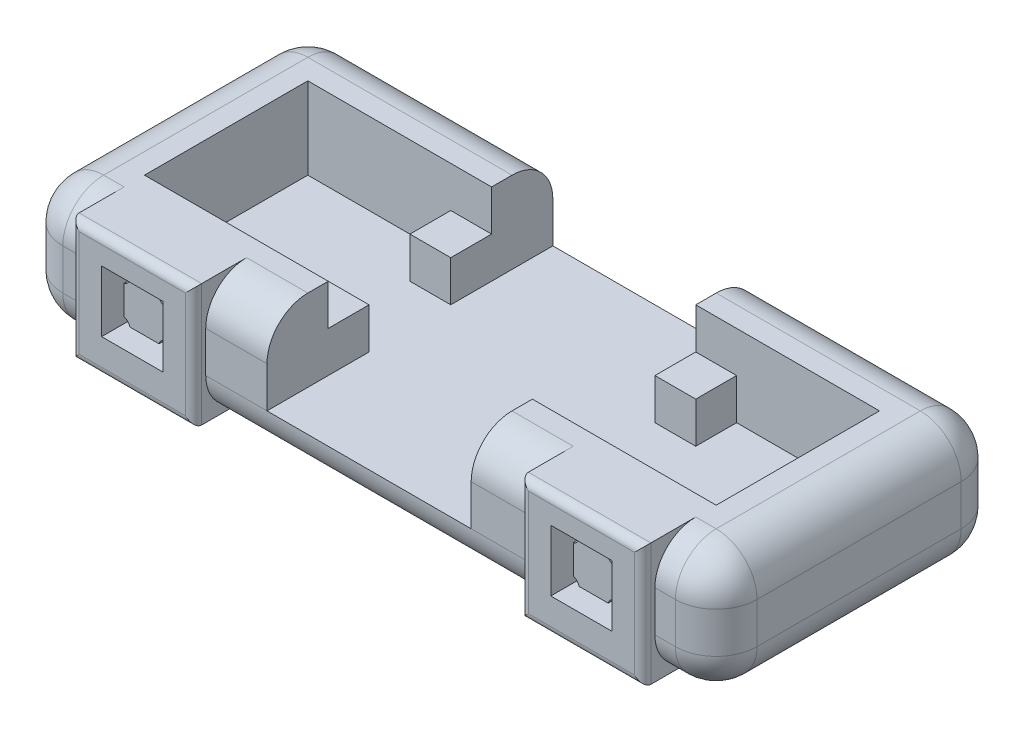
SolidWorks part; units mm, degrees
ref_plane "Front Plane" through (0, 0, 0) normal (0, 0, 1) x (1, 0, 0)
ref_plane "Top Plane" through (0, 0, 0) normal (0, 1, 0) x (1, 0, 0)
ref_plane "Right Plane" through (0, 0, 0) normal (1, 0, 0) x (0, 0, -1)
sketch "Sketch1" plane through (0, 0, 0) normal (0, 1, 0) x (1, 0, 0)
  line L1 (-85, -35) -> (85, -35)
  line L2 (-85, -35) -> (-85, 35)
  line L3 (-85, 35) -> (85, 35)
  line L4 (85, -35) -> (85, 35)
  line L5 (-85, -35) -> (85, 35) construction
  line L6 (-85, 35) -> (85, -35) construction
  point P0 (0, 0)
  dimension "D1" = 170
  dimension "D2" = 70
extrude "Boss-Extrude1" add sketch "Sketch1" along normal blind 30
fillet "Fillet1" radius 10 12 edges at (-85, 30, 0) (0, 30, 35) (-85, 15, 35) (85, 0, 0) (0, 0, -35) (-85, 0, 0) (0, 0, 35) (85, 30, 0) (0, 30, -35) (85, 15, 35) (-85, 15, -35) (85, 15, -35)
sketch "Sketch2" plane through (0, 30, 0) normal (0, 1, 0) x (1, 0, 0)
  line L0 (-75, 35) -> (75, 35) construction
  line L1 (25, -35) -> (-25, -35)
  line L2 (25, -35) -> (25, 35)
  line L3 (25, 35) -> (-25, 35)
  line L4 (-25, -35) -> (-25, 35)
  line L5 (25, -35) -> (-25, 35) construction
  line L6 (25, 35) -> (-25, -35) construction
  line L8 (70, -20) -> (-70, -20)
  line L9 (70, -20) -> (70, 20)
  line L10 (70, 20) -> (-70, 20)
  line L11 (-70, -20) -> (-70, 20)
  line L12 (70, -20) -> (-70, 20) construction
  line L13 (70, 20) -> (-70, -20) construction
  point P0 (0, 0)
  point P8 (0, 0)
  line M9 (75, 25) -> (-75, 25)
  line M11 (-75, -25) -> (75, -25)
  dimension "D1" = 50
  dimension "D2" = 140
  dimension "D3" = 40
extrude "Cut-Extrude1" cut sketch "Sketch2" against normal blind 20 contours L11 L8 L4 L10 | L2 L10 L4 L8 | L9 L10 L2 L8 | L4 L2 L3 M9 | L10 L2 L4 M9 | L4 L1 L2 M11 | L2 L8 L4 M11
sketch "Sketch3" plane through (0, 10, 0) normal (0, 1, 0) x (1, 0, 0)
  line L1 (-25, 20) -> (-35, 20)
  line L2 (-25, 20) -> (-25, 10)
  line L3 (-25, 10) -> (-35, 10)
  line L4 (-35, 20) -> (-35, 10)
  line L5 (25, 20) -> (35, 20)
  line L6 (25, 20) -> (25, 10)
  line L7 (25, 10) -> (35, 10)
  line L8 (35, 20) -> (35, 10)
  line L9 (25, -20) -> (35, -20)
  line L10 (25, -20) -> (25, -10)
  line L11 (25, -10) -> (35, -10)
  line L12 (35, -20) -> (35, -10)
  line L13 (-25, -20) -> (-35, -20)
  line L14 (-25, -20) -> (-25, -10)
  line L15 (-25, -10) -> (-35, -10)
  line L16 (-35, -20) -> (-35, -10)
  dimension "D1" = 10
  dimension "D2" = 10
  dimension "D3" = 10
  dimension "D4" = 10
  dimension "D5" = 10
  dimension "D6" = 10
  dimension "D7" = 10
  dimension "D8" = 10
extrude "Boss-Extrude2" add sketch "Sketch3" along normal blind 10
sketch "Sketch4" plane through (0, 0, 35) normal (0, 0, 1) x (1, 0, 0)
  line L0 (-25, 10) -> (-25, 20) construction
  line L2 (0, 0) -> (0, 30) construction
  line L3 (40, 30) -> (70, 30)
  line L4 (70, 0) -> (70, 30)
  line L5 (40, 0) -> (70, 0)
  line L6 (40, 0) -> (40, 30)
  line L8 (-68.0808, 30) -> (-70, 30)
  line L9 (-75, 30) -> (-25, 30) construction
  line L14 (-40, 0) -> (-70, 0)
  line L15 (-40, 0) -> (-40, 30)
  line L16 (-40, 30) -> (-70, 30)
  line L17 (-70, 0) -> (-70, 30)
  point P10 (-55, 15)
  line M6 (75, 20) -> (25, 20)
  line M8 (25, 10) -> (75, 10)
  dimension "D1" = 30
  dimension "D2" = 30
  dimension "D3" = 15
extrude "Boss-Extrude3" add sketch "Sketch4" along normal blind 3 contours L17 L14 L15 L16 L8 | L6 L4 M8 M6 | L6 L4 L3 M6 | L6 L5 L4 M8
sketch "Sketch5" plane through (0, 0, 35) normal (0, 0, -1) x (-1, 0, 0)
  line L1 (-70, 30) -> (-40, 30)
  line L2 (-70, 30) -> (-70, 0)
  line L3 (-70, 0) -> (-40, 0)
  line L4 (-40, 30) -> (-40, 0)
  line L5 (40, 0) -> (70, 0)
  line L6 (40, 0) -> (40, 30)
  line L7 (40, 30) -> (70, 30)
  line L8 (70, 0) -> (70, 30)
extrude "Boss-Extrude4" add sketch "Sketch5" along normal blind 10
fillet "Fillet2" radius 2 8 edges at (-55, 30, 38) (-40, 15, 38) (-55, 0, 38) (-70, 15, 38) (55, 30, 38) (70, 15, 38) (55, 0, 38) (40, 15, 38)
sketch "Sketch6" plane through (0, 0, 38) normal (0, 0, 1) x (1, 0, 0)
  line L0 (-70, 30) -> (-40, 30) construction
  line L1 (-47.5, 8.5) -> (-62.5, 8.5)
  line L2 (-47.5, 8.5) -> (-47.5, 23.5)
  line L7 (-47.5, 23.5) -> (-62.5, 23.5)
  line L8 (-62.5, 8.5) -> (-62.5, 23.5)
  line L13 (-47.5, 8.5) -> (-62.5, 23.5) construction
  line L14 (-47.5, 23.5) -> (-62.5, 8.5) construction
  line L16 (0, 0) -> (0, 27.2097) construction
  line L17 (47.5, 23.5) -> (62.5, 23.5)
  line L18 (62.5, 8.5) -> (62.5, 23.5)
  line L19 (47.5, 8.5) -> (62.5, 8.5)
  line L20 (47.5, 8.5) -> (47.5, 23.5)
  line L21 (-70, 10) -> (-70, 20) construction
  point P0 (-55, 16)
  point P8 (-55, 16)
  dimension "D1" = 15
  dimension "D2" = 15
  dimension "D3" = 6.5
  dimension "D4" = 7.5
extrude "Cut-Extrude2" cut sketch "Sketch6" against normal blind 10
sketch "Sketch7" plane through (0, 0, 28) normal (0, 0, 1) x (1, 0, 0)
  line L0 (-62.5, 8.5) -> (-47.5, 23.5) construction
  line L1 (-62.5, 23.5) -> (-47.5, 8.5) construction
  line L2 (0, 0) -> (0, 29.8269) construction
  line L3 (-50, 11) -> (-60, 11)
  line L4 (-50, 11) -> (-50, 21)
  line L5 (-50, 21) -> (-60, 21)
  line L6 (-60, 11) -> (-60, 21)
  line L7 (-50, 11) -> (-60, 21) construction
  line L8 (-50, 21) -> (-60, 11) construction
  line L9 (40, 0) -> (-40, 0) construction
  line L10 (50, 21) -> (60, 21)
  line L11 (60, 11) -> (60, 21)
  line L12 (50, 11) -> (60, 11)
  line L13 (50, 11) -> (50, 21)
  point P8 (-55, 16)
  dimension "D1" = 10
extrude "Boss-Extrude5" add sketch "Sketch7" along normal blind 7
sketch "Sketch8" plane through (0, 0, 28) normal (0, 0, 1) x (1, 0, 0)
  line L2 (47.5, 23.5) -> (47.5, 8.5) construction
  line L3 (62.5, 23.5) -> (47.5, 23.5) construction
  line L4 (62.5, 23.5) -> (47.5, 23.5) construction
  line L6 (62.5, 8.5) -> (62.5, 23.5) construction
  line L7 (47.5, 8.5) -> (62.5, 8.5) construction
  line L8 (47.5, 23.5) -> (47.5, 8.5) construction
  line L9 (47.5, 8.5) -> (62.5, 8.5) construction
  line L10 (0, 0) -> (0, 30.3659) construction
  circle A0 centre (49.5, 21.5) radius 2
  circle A1 centre (49.5, 10.5) radius 2
  circle A2 centre (60.5, 21.5) radius 2
  circle A3 centre (60.5, 10.5) radius 2
  circle A4 centre (-60.5, 10.5) radius 2
  circle A5 centre (-49.5, 10.5) radius 2
  circle A6 centre (-60.5, 21.5) radius 2
  circle A7 centre (-49.5, 21.5) radius 2
  dimension "D1" = 4
  dimension "D2" = 4
  dimension "D3" = 4
  dimension "D4" = 4
extrude "Cut-Extrude3" cut sketch "Sketch8" against normal blind 13 and the other way blind 7
sketch "Sketch9" plane through (0, 0, 0) normal (0, -1, 0) x (1, 0, 0)
  line L0 (-40, 35) -> (-25, 35) construction
  line L1 (30, -35) -> (-30, -35)
  line L2 (30, -35) -> (30, 35)
  line L3 (30, 35) -> (-30, 35)
  line L4 (-30, -35) -> (-30, 35)
  line L5 (30, -35) -> (-30, 35) construction
  line L6 (30, 35) -> (-30, -35) construction
  point P0 (0, 0)
  dimension "D1" = 60
extrude "Cut-Extrude4" cut sketch "Sketch9" against normal blind 2
